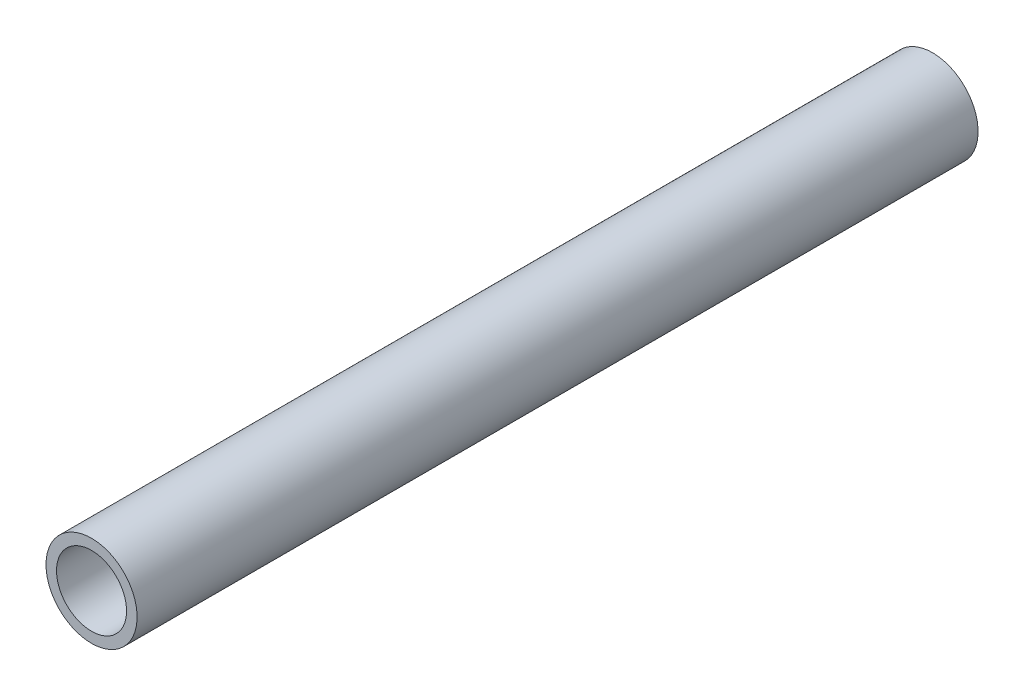
SolidWorks part; units mm, degrees
ref_plane "Front Plane" through (0, 0, 0) normal (0, 0, 1) x (1, 0, 0)
ref_plane "Top Plane" through (0, 0, 0) normal (0, 1, 0) x (1, 0, 0)
ref_plane "Right Plane" through (0, 0, 0) normal (1, 0, 0) x (0, 0, -1)
sketch "Sketch1" plane through (0, 0, 0) normal (0, 0, 1) x (1, 0, 0)
  circle A0 centre (0, 0) radius 16.51
  circle A1 centre (0, 0) radius 12.7
  dimension "D1" = 33.02
  dimension "D2" = 25.4
extrude "Boss-Extrude1" add sketch "Sketch1" along normal blind 304.8
ref_plane "Fitting2" through (0, 0, 304.8) normal (0, 0, 1) x (1, 0, 0)
ref_plane "Fitting1" through (0, 0, 0) normal (0, 0, 1) x (1, 0, 0)
